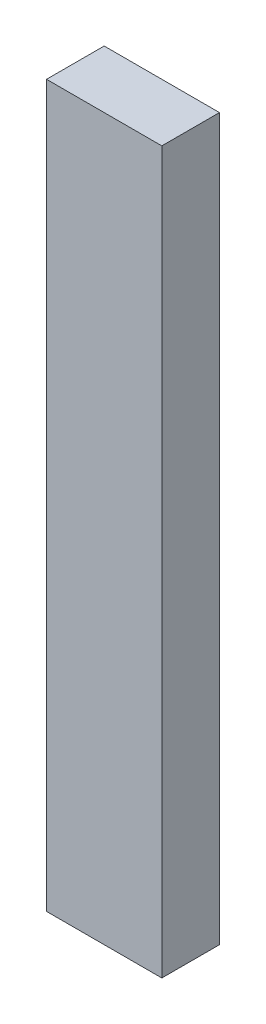
SolidWorks part; units mm, degrees
ref_plane "Front Plane" through (0, 0, 0) normal (0, 0, 1) x (1, 0, 0)
ref_plane "Top Plane" through (0, 0, 0) normal (0, 1, 0) x (1, 0, 0)
ref_plane "Right Plane" through (0, 0, 0) normal (1, 0, 0) x (0, 0, -1)
sketch "Sketch1" plane through (0, 0, 0) normal (0, 1, 0) x (1, 0, 0)
  line L1 (25, -25) -> (-25, -25)
  line L2 (25, -25) -> (25, 25)
  line L3 (25, 25) -> (-25, 25)
  line L4 (-25, -25) -> (-25, 25)
  line L5 (25, -25) -> (-25, 25) construction
  line L6 (25, 25) -> (-25, -25) construction
  point P0 (0, 0)
  dimension "D1" = 50
  dimension "D2" = 50
ref_plane "Plane1" through (0, 1, 0) normal (0, 1, 0) x (1, 0, 0)
sketch "Sketch5" plane through (0, 1, 0) normal (0, 1, 0) x (1, 0, 0)
  line L0 (-25, -25) -> (-25, 25) construction
  line L1 (-4, 2) -> (4, 2)
  line L2 (-4, 2) -> (-4, -2)
  line L3 (-4, -2) -> (4, -2)
  line L4 (4, 2) -> (4, -2)
  line L6 (25, 25) -> (-25, 25) construction
  dimension "D1" = 4
  dimension "D2" = 8
  dimension "D3" = 21
  dimension "D4" = 23
extrude "Boss-Extrude4" add sketch "Sketch5" along normal blind 50 separate body
